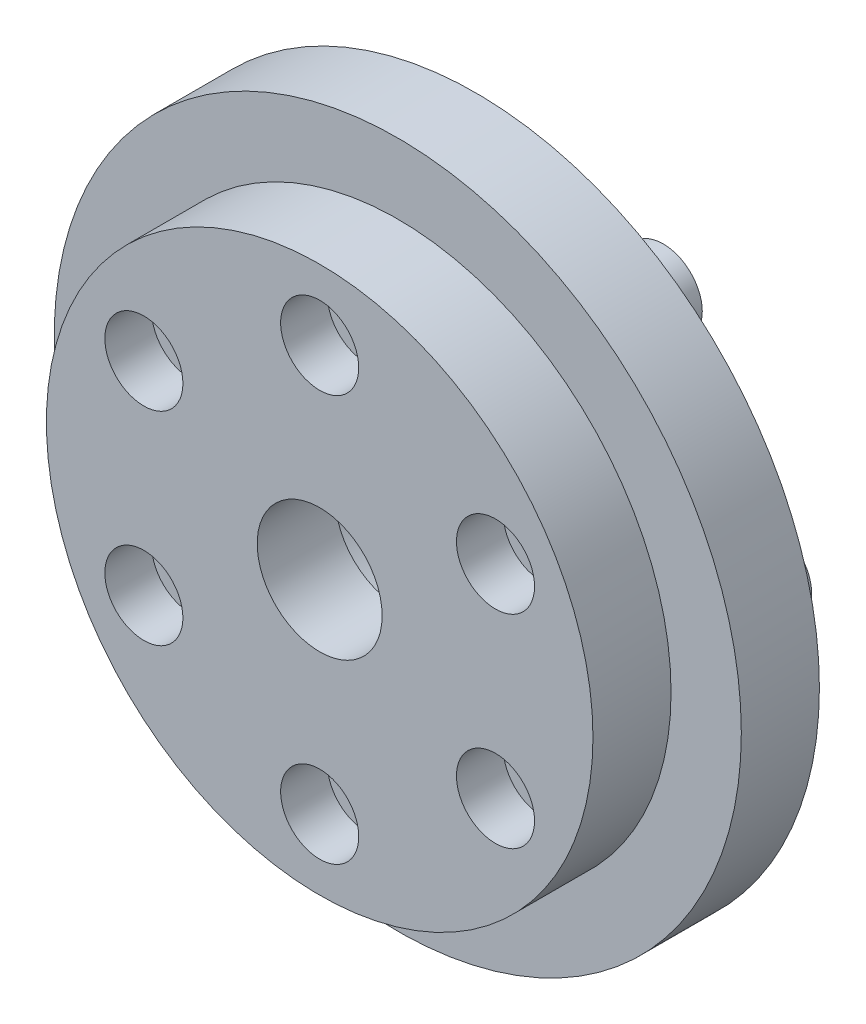
SolidWorks part; units mm, degrees
ref_plane "Front Plane" through (0, 0, 0) normal (0, 0, 1) x (1, 0, 0)
ref_plane "Top Plane" through (0, 0, 0) normal (0, 1, 0) x (1, 0, 0)
ref_plane "Right Plane" through (0, 0, 0) normal (1, 0, 0) x (0, 0, -1)
sketch "Model" plane through (0, 0, 0) normal (0, 0, 1) x (1, 0, 0)
  circle A0 centre (14, 0) radius 2.5
  circle A1 centre (7, 12.1244) radius 2.5
  circle A2 centre (-7, 12.1244) radius 2.5
  circle A3 centre (-14, 0) radius 2.5
  circle A4 centre (-7, -12.1244) radius 2.5
  circle A5 centre (7, -12.1244) radius 2.5
sketch "Sketch2" plane through (0, 0, 0) normal (0, 0, 1) x (1, 0, 0)
  circle A0 centre (-7, 12.1244) radius 2.5
  circle A1 centre (7, 12.1244) radius 2.5
  circle A2 centre (14, 0) radius 2.5
  circle A3 centre (7, -12.1244) radius 2.5
  circle A4 centre (-7, -12.1244) radius 2.5
  circle A5 centre (-14, 0) radius 2.5
  point P15 (0, 0)
  dimension "D1" = 5
  dimension "D2" = 6
extrude "Boss-Extrude1" add sketch "Sketch2" along normal blind 5
sketch "Sketch3" plane through (0, 0, 5) normal (0, 0, 1) x (1, 0, 0)
  circle A0 centre (0, 0) radius 22
  dimension "D1" = 44
extrude "Boss-Extrude2" add sketch "Sketch3" along normal blind 5
sketch "Sketch4" plane through (0, 0, 10) normal (0, 0, 1) x (1, 0, 0)
  circle A0 centre (0, 0) radius 17.5
  dimension "D1" = 35
extrude "Boss-Extrude3" add sketch "Sketch4" along normal blind 5
sketch "Sketch5" plane through (0, 0, 15) normal (0, 0, 1) x (1, 0, 0)
  circle A0 centre (0, 0) radius 8
  dimension "D1" = 16
extrude "Cut-Extrude1" cut sketch "Sketch5" against normal up to surface (10 mm away) up to face at (-11.5, 0, 5)
sketch "Sketch11" plane through (0, 0, 15) normal (0, 0, 1) x (1, 0, 0)
  circle A0 centre (0, 13) radius 2.5
  circle A1 centre (11.2583, 6.5) radius 2.5
  circle A2 centre (11.2583, -6.5) radius 2.5
  circle A3 centre (0, -13) radius 2.5
  circle A4 centre (-11.2583, -6.5) radius 2.5
  circle A5 centre (-11.2583, 6.5) radius 2.5
  point P15 (0, 0)
  dimension "D1" = 5
  dimension "D2" = 13
  dimension "D3" = 6
extrude "Cut-Extrude4" cut sketch "Sketch11" against normal blind 3
sketch "Sketch13" plane through (0, 0, 15) normal (0, 0, 1) x (1, 0, 0)
  circle A0 centre (0, 0) radius 8
  circle A1 centre (0, 0) radius 4
  dimension "D1" = 8
extrude "Boss-Extrude5" add sketch "Sketch13" against normal blind 5
